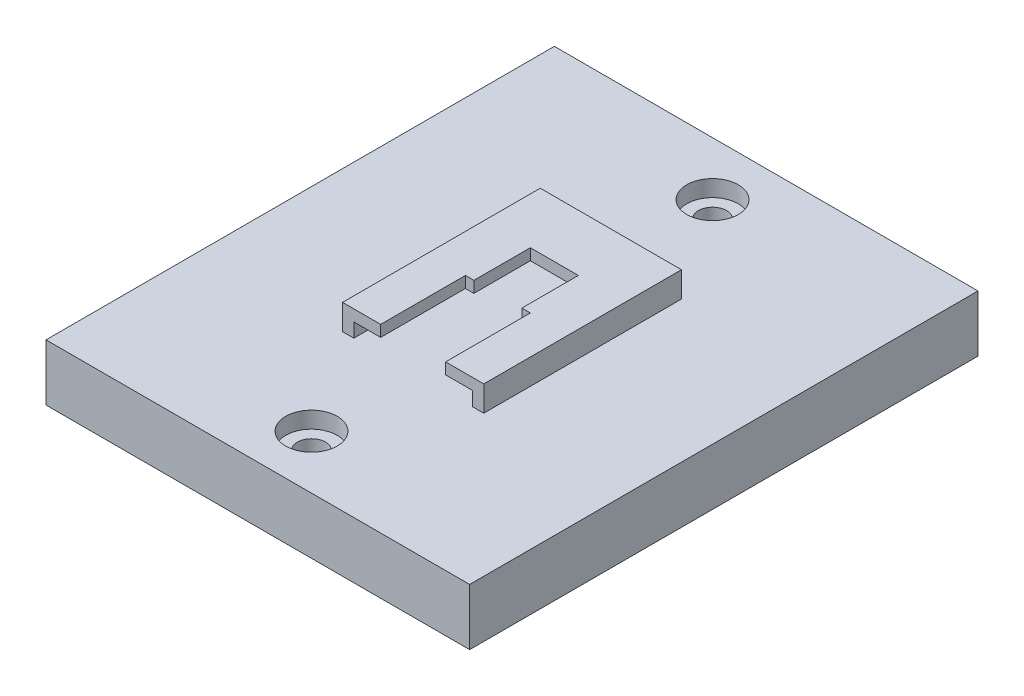
SolidWorks part; units mm, degrees
ref_plane "Front Plane" through (0, 0, 0) normal (0, 0, 1) x (1, 0, 0)
ref_plane "Top Plane" through (0, 0, 0) normal (0, 1, 0) x (1, 0, 0)
ref_plane "Right Plane" through (0, 0, 0) normal (1, 0, 0) x (0, 0, -1)
sketch "Sketch1" plane through (0, 0, 0) normal (0, 1, 0) x (1, 0, 0)
  line L0 (0, 23.0591) -> (0, -29.2863) construction
  line L1 (-12.5, 17.5) -> (12.5, 17.5)
  line L2 (-12.5, 17.5) -> (-12.5, -17.5)
  line L3 (-12.5, -17.5) -> (12.5, -17.5)
  line L4 (12.5, 17.5) -> (12.5, -17.5)
  line L5 (-12.5, 17.5) -> (12.5, -17.5) construction
  line L6 (-12.5, -17.5) -> (12.5, 17.5) construction
  line L7 (-5.75, -17.5) -> (5.75, -17.5)
  line L8 (-5.75, -17.5) -> (-5.75, -2.5)
  line L9 (-5.75, -2.5) -> (5.75, -2.5)
  line L10 (5.75, -17.5) -> (5.75, -2.5)
  line L11 (-4.25, -2.5) -> (4.25, -2.5)
  line L12 (-4.25, -2.5) -> (-4.25, 7.5)
  line L13 (-4.25, 7.5) -> (4.25, 7.5)
  line L14 (4.25, -2.5) -> (4.25, 7.5)
  point P0 (0, 0)
  dimension "D1" = 25
  dimension "D2" = 35
  dimension "D3" = 11.5
  dimension "D4" = 8.5
  dimension "D5" = 15
  dimension "D6" = 25
extrude "Boss-Extrude1" add sketch "Sketch1" along normal blind 2 contours L14 L9 L10 L3 L4 L1 L2 L8 L12 L13
sketch "Sketch2" plane through (0, 0, 0) normal (0, -1, 0) x (1, 0, 0)
  line L0 (-12.5, 17.5) -> (-12.5, -17.5)
  line L1 (-12.5, -17.5) -> (12.5, -17.5)
  line L2 (12.5, -17.5) -> (12.5, 17.5)
  line L3 (12.5, 17.5) -> (10.5, 17.5)
  line L4 (5.75, 17.5) -> (12.5, 17.5) construction
  line L5 (10.5, 17.5) -> (10.5, -15.5)
  line L6 (10.5, -15.5) -> (-10.5, -15.5)
  line L7 (-10.5, -15.5) -> (-10.5, 17.5)
  line L8 (-12.5, 17.5) -> (-5.75, 17.5) construction
  line L9 (-10.5, 17.5) -> (-12.5, 17.5)
  dimension "D1" = 2
  dimension "D2" = 2
  dimension "D3" = 2
extrude "Boss-Extrude2" add sketch "Sketch2" along normal blind 2.5
sketch "Sketch3" plane through (0, -2.5, 0) normal (0, -1, 0) x (1, 0, 0)
  line L1 (-37.5, 45) -> (37.5, 45)
  line L2 (-37.5, 45) -> (-37.5, -45)
  line L3 (-37.5, -45) -> (37.5, -45)
  line L4 (37.5, 45) -> (37.5, -45)
  line L5 (-37.5, 45) -> (37.5, -45) construction
  line L6 (-37.5, -45) -> (37.5, 45) construction
  point P0 (0, 0)
  dimension "D1" = 75
  dimension "D2" = 90
extrude "Boss-Extrude3" add sketch "Sketch3" along normal blind 10
sketch "Sketch4" plane through (0, -2.5, 0) normal (0, 1, 0) x (1, 0, 0)
  line L0 (0, 52.8403) -> (0, -58.1898) construction
  line L1 (-26, 26) -> (26, 26) construction
  line L2 (-26, 26) -> (-26, -26) construction
  line L3 (-26, -26) -> (26, -26) construction
  line L4 (26, 26) -> (26, -26) construction
  line L5 (-26, 26) -> (26, -26) construction
  line L6 (-26, -26) -> (26, 26) construction
  line L7 (-11.2462, 35.5) -> (11.9137, 35.5) construction
  line L10 (-37.5, 45) -> (37.5, 45) construction
  line L11 (-55, 0) -> (55, 0) construction
  line L12 (-11.2462, -35.5) -> (11.9137, -35.5) construction
  point P0 (0, 0)
  dimension "D1" = 52
  dimension "D2" = 52
  dimension "D3" = 9.5
hole_wizard "CBORE for #8 Pan Head Machine Screw1" positions "Sketch5" profile "Sketch6" counterbore size "#8" standard "ANSI Inch" end condition through all
sketch "Sketch5" plane through (0, -2.5, 0) normal (0, 1, 0) x (1, 0, 0)
  line L0 (0, 52.8403) -> (0, -58.1898) construction
  line L1 (-11.2462, 35.5) -> (11.9137, 35.5) construction
  line L2 (-11.2462, -35.5) -> (11.9137, -35.5) construction
  point P0 (0, 35.5)
  point P6 (0, -35.5)
sketch "Sketch6" plane through (0, -2.5, -35.5) normal (1, 0, 0) x (0, 0, 1)
  line L0 (0, 0) -> (0, 10)
  line L1 (0, 10) -> (2.4892, 10)
  line L3 (2.4892, 10) -> (2.4892, 2.921)
  line L4 (2.4892, 2.921) -> (4.5644, 2.921)
  line L5 (4.5644, 2.921) -> (4.5644, 0)
  line L7 (4.5644, 0) -> (0, 0)
  line L11 (0, -6.35) -> (0, 107.95) construction
  dimension "Thru Hole Dia." = 4.9784
  dimension "Thru Hole Depth" = 10
  dimension "C'Bore Dia." = 9.1288
  dimension "C'Bore Depth" = 2.921
